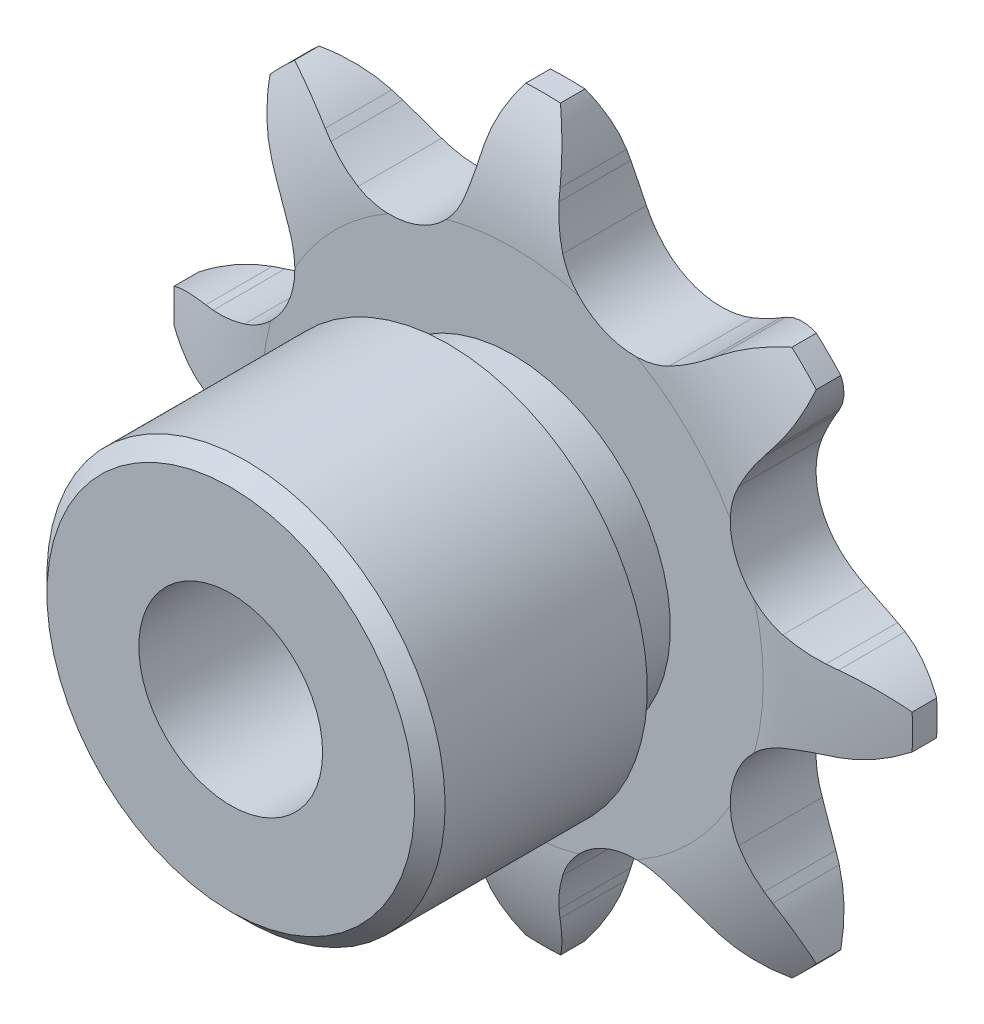
SolidWorks part; units mm, degrees
ref_plane "Front Plane" through (0, 0, 0) normal (0, 0, 1) x (1, 0, 0)
ref_plane "Top Plane" through (0, 0, 0) normal (0, 1, 0) x (1, 0, 0)
ref_plane "Right Plane" through (0, 0, 0) normal (1, 0, 0) x (0, 0, -1)
sketch "Sketch0" plane through (0, 0, 0) normal (0, 0, 1) x (1, 0, 0)
  line L0 (4, -9.6569) -> (0, 0) construction
  line L1 (0, 0) -> (9.6569, -4) construction
  line L2 (0, 0) -> (-4, -9.6569) construction
  line L3 (4, -9.6569) -> (9.6569, -4) construction
  line L4 (4, -9.6569) -> (-4, -9.6569) construction
  line L5 (6.4283, -8.1776) -> (6.1599, -7.9825)
  line L6 (4, -9.6569) -> (0, -11.3137) construction
  line L7 (1.2369, -10.3279) -> (1.2888, -10.0002)
  line L8 (0, -9.6569) -> (0, -12.0569) construction
  line L9 (5.0779, -7.3452) -> (2.3095, -13.2821) construction
  line L10 (0, 0) -> (0, -9.6569) construction
  line L11 (6.1599, -7.9825) -> (2.3095, -13.2821) construction
  line L12 (0, -12.0569) -> (0, -12.7231) construction
  line L13 (8.9497, -4.7071) -> (6.4283, -8.1776) construction
  circle A0 centre (0, 0) radius 12.0569 construction
  circle A1 centre (0, 0) radius 10.4525 construction
  arc A2 (-4.2727, -13.7535) -> (12.7464, -6.7039) centre (0, 0) ccw
  circle A3 centre (0, 0) radius 12.7231 construction
  circle A4 centre (4, -9.6569) radius 2.5 construction
  arc A7 (5.0779, -7.3452) -> (1.6032, -8.7845) centre (4, -9.6569) ccw
  circle A8 centre (4, -9.6569) radius 2.5506 construction
  arc A9 (6.4283, -8.1776) -> (12.7464, -6.7039) centre (8.9497, -4.7071) ccw
  arc A10 (6.1599, -7.9825) -> (5.0779, -7.3452) centre (2.3095, -13.2821) ccw
  arc A11 (1.2369, -10.3279) -> (-4.2727, -13.7535) centre (-3, -9.6569) cw
  arc A12 (1.2888, -10.0002) -> (1.6032, -8.7845) centre (7.7588, -11.0249) cw
  dimension "D1" = 2.5506
  dimension "Dr" = 5
  dimension "Ds" = 5.1012
  dimension "R" = 2.5506
  dimension "Pitch" = 8
  dimension "A" = 42.5
  dimension "360/N" = 45
  dimension "B" = 11
  dimension "ab" = 7
  dimension "J" = 2.4
  dimension "ac" = 4
sketch "Sketch1" plane through (0, 0, 0) normal (1, 0, 0) x (0, 0, -1)
  line L0 (1.4, 0) -> (-1.4, 0)
  line L1 (-1.4, 0) -> (-1.4, 8.1839)
  line L2 (-1.4, 10.4525) -> (0, 10.4525) construction
  line L3 (-0.4, 12.0569) -> (0.4, 12.0569)
  line L5 (1.4, 8.1839) -> (1.4, 0)
  line L7 (0, 12.0569) -> (0, 0) construction
  line L8 (-1.4, 8.1839) -> (1.4, 8.1839) construction
  line L9 (0, 12.0569) -> (0, -12.0569) construction
  line L10 (-1.4, 8.1839) -> (-1.4, 12.0569) construction
  line L11 (-1.4, 12.0569) -> (-0.4, 12.0569) construction
  line L12 (0.4, 12.0569) -> (1.4, 12.0569) construction
  line L13 (1.4, 12.0569) -> (1.4, 8.1839) construction
  line L14 (0, 0) -> (-6.4008, 0) construction
  line L15 (-1.4, 10.4525) -> (-1.4, 5.1525) construction
  line L22 (1.4, 0) -> (-10.6, 0) construction
  line L24 (-1.4, 0) -> (-1.4, 5.1525) construction
  arc A0 (-0.4, 12.0569) -> (-1.4, 8.1839) centre (6.6, 8.1839) ccw
  arc A1 (0.4, 12.0569) -> (1.4, 8.1839) centre (-6.6, 8.1839) cw
  dimension "R" = 8
  dimension "t" = 2.8
  dimension "C" = 1
  dimension "A" = 3.873
  dimension "K" = 6.4008
  dimension "Width" = 12
  dimension "H" = 5.3
revolve "Revolve1" add sketch "Sketch1" angle 360 about L0
extrude "Cut-Extrude1" cut sketch "Sketch0" against normal through all and the other way through all
pattern_circular "CirPattern1" count 8 over 360 about axis through (0, 0, 0) along (0, 0, 1) of "Cut-Extrude1"
sketch "Sketch2" plane through (0, 0, 0) normal (0, 0, 1) x (1, 0, 0)
  circle A0 centre (0, 0) radius 3 construction
  circle A1 centre (0, 0) radius 6.5
  circle A2 centre (0, 0) radius 12.055 construction
  dimension "Bore" = 6
  dimension "Hub Dia." = 13
  dimension "OD" = 24.11
extrude "Boss-Extrude1" add sketch "Sketch2" along normal up to vertex (10.6 mm away) from surface at 1.4 starting at face at (0, 0, 1.4)
sketch "Sketch3" plane through (0, 0, 0) normal (0, 0, 1) x (1, 0, 0)
  circle A0 centre (0, 0) radius 3 construction
  circle A1 centre (0, 0) radius 3
extrude "Cut-Extrude2" cut sketch "Sketch3" along normal through all and the other way through all
sketch "Sketch4" plane through (0, 0, 0) normal (1, 0, 0) x (0, 0, -1)
  line L0 (-10.6, 6.5) -> (-10.6, 6)
  line L1 (-1.4, 12.0569) -> (-3.5, 12.0569)
  line L2 (-1.4, 12.0569) -> (-1.4, 5.1525)
  line L3 (-1.4, 5.1525) -> (-3.5, 5.1525)
  line L4 (-3.5, 12.0569) -> (-3.5, 5.1525)
  line L9 (-10.6, 6) -> (-10.1, 6.5)
  line L10 (-10.1, 6.5) -> (-10.6, 6.5)
  dimension "C" = 0.5
  dimension "D3" = 2.1
revolve "Cut-Revolve1" cut sketch "Sketch4" angle 360 about L22
sketch "Sketch5" plane through (0, 0, 0) normal (0, 0, 1) x (1, 0, 0)
  circle A0 centre (0, 0) radius 12.055 construction
  circle A1 centre (0, 0) radius 12.055
extrude "Cut-Extrude3" [suppressed] cut sketch "Sketch5" against normal through all and the other way through all flip side to cut
equation "\"360/N@Sketch0\" = 360/\"Teeth@CirPattern1\""
equation "\"Ds@Sketch0\" = 1.005 * \"Dr@Sketch0\" + ( 0.003 * 25.4 ) "
equation "\"R@Sketch0\" = 1/2 * \"Ds@Sketch0\""
equation "\"A@Sketch0\" = 35 +  ( 60 / \"Teeth@CirPattern1\" ) "
equation "\"B@Sketch0\" = 18 -  ( 56 / \"Teeth@CirPattern1\" )"
equation "\"ac@Sketch0\" = 0.8 * \"Dr@Sketch0\""
equation "\"ab@Sketch0\" = 1.4 * \"Dr@Sketch0\""
equation "\"J@Sketch0\" = 0.3 * \"Pitch@Sketch0\""
equation "\"D3@Sketch4\" = \"t@Sketch1\" * 3 / 4"
